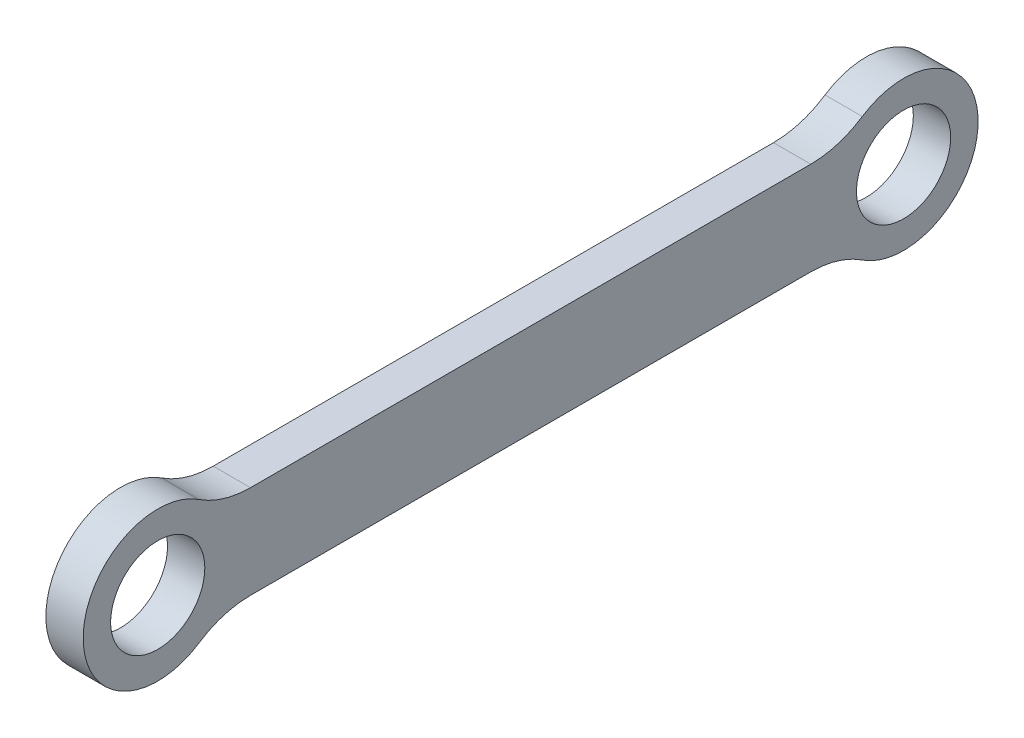
SolidWorks part; units mm, degrees
ref_plane "Plan de face" through (0, 0, 0) normal (0, 0, 1) x (1, 0, 0)
ref_plane "Plan de dessus" through (0, 0, 0) normal (0, 1, 0) x (1, 0, 0)
ref_plane "Plan de droite" through (0, 0, 0) normal (1, 0, 0) x (0, 0, -1)
sketch "Esquisse1" plane through (0, 0, 0) normal (1, 0, 0) x (0, 0, -1)
  line L0 (-47.7273, 0) -> (57.7273, 0) construction
  line L1 (40, 0) -> (-40, 0) construction
  line L2 (40, -8) -> (-40, -8) construction
  line L3 (40, 8) -> (-40, 8) construction
  line L4 (0, 18.828) -> (0, -23.0645) construction
  line L5 (33.755, 5) -> (-33.755, 5)
  line L6 (33.755, -5) -> (-33.755, -5)
  arc A0 (40, -8) -> (40, 8) centre (40, 0) ccw construction
  arc A1 (-40, 8) -> (-40, -8) centre (-40, 0) ccw construction
  circle A2 centre (-40, 0) radius 8 construction
  arc A3 (-33.755, 5) -> (-33.755, -5) centre (-40, 0) ccw
  arc A4 (33.755, 5) -> (33.755, -5) centre (40, 0) cw
  point P5 (0, 0)
  point P20 (0, -5)
  point P22 (0, 5)
  dimension "D3" = 10
  dimension "D1" = 80
  dimension "D2" = 16
extrude "Boss.-Extru.1" add sketch "Esquisse1" along normal blind 4 contours A4 L5 A3 L6
sketch "Esquisse2" plane through (4, 0, 0) normal (1, 0, 0) x (0, 0, -1)
  line L2 (33.755, 5) -> (-33.755, 5)
  line L3 (-33.755, -5) -> (33.755, -5)
  line L4 (33.755, 5) -> (-33.755, 5)
  line L5 (-33.755, -5) -> (33.755, -5)
  circle A0 centre (-40, 0) radius 5.05
  circle A1 centre (40, 0) radius 5.05
  arc A2 (33.755, -5) -> (33.755, 5) centre (40, 0) ccw
  arc A3 (-33.755, 5) -> (-33.755, -5) centre (-40, 0) ccw
  arc A4 (33.755, -5) -> (33.755, 5) centre (40, 0) ccw
  arc A5 (-33.755, 5) -> (-33.755, -5) centre (-40, 0) ccw
  dimension "D2" = 10.1
  dimension "D1" = 0
extrude "Enlèv. mat.-Extru.1" cut sketch "Esquisse2" against normal blind 10 contours A0 | A1
fillet "Congé1" radius 10 4 edges at (2, 5, -33.755) (2, 5, 33.755) (2, -5, -33.755) (2, -5, 33.755)
